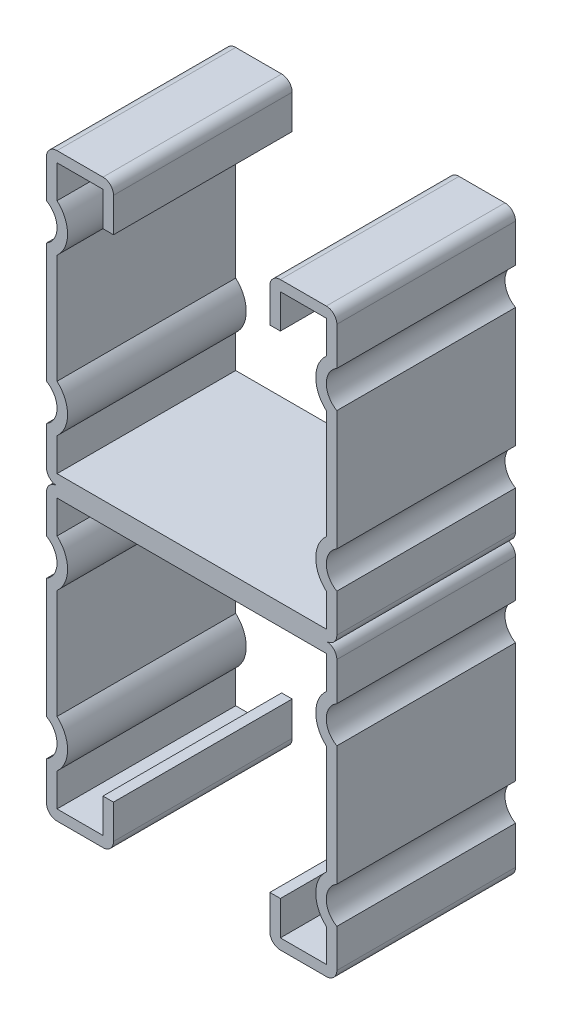
SolidWorks part; units mm, degrees
ref_plane "Plane1" through (0, 0, 0) normal (0, 0, 1) x (1, 0, 0)
ref_plane "Plane2" through (0, 0, 0) normal (0, 1, 0) x (1, 0, 0)
ref_plane "Plane3" through (0, 0, 0) normal (1, 0, 0) x (0, 0, -1)
sketch "Sketch1" plane through (0, 0, 0) normal (0, 0, 1) x (1, 0, 0)
  line L0 (-41.275, 39.7764) -> (-41.275, 34.3457)
  line L1 (-41.275, 29.1543) -> (-41.275, 12.1207)
  line L2 (-39.7764, 0) -> (-1.4986, 0)
  line L3 (0, 1.4986) -> (0, 6.9293)
  line L4 (0, 34.3457) -> (0, 39.7764)
  line L5 (-1.4986, 41.275) -> (-8.0264, 41.275)
  line L6 (-9.525, 39.7764) -> (-9.525, 34.925)
  line L7 (-39.7764, 41.275) -> (-33.2486, 41.275)
  line L8 (-31.75, 39.7764) -> (-31.75, 34.925)
  line L9 (-1.4986, 6.174) -> (-1.4986, 35.101) construction
  line L10 (-39.7764, 35.101) -> (-39.7764, 6.174) construction
  line L11 (-33.2486, 39.7764) -> (-33.2486, 34.925)
  line L12 (-39.7764, 39.7764) -> (-33.2486, 39.7764)
  line L13 (-39.7764, 39.7764) -> (-39.7764, 35.101)
  line L14 (-39.7764, 28.399) -> (-39.7764, 12.876)
  line L15 (-39.7764, 1.4986) -> (-1.4986, 1.4986)
  line L16 (-1.4986, 1.4986) -> (-1.4986, 6.174)
  line L17 (-1.4986, 35.101) -> (-1.4986, 39.7764)
  line L18 (-1.4986, 39.7764) -> (-8.0264, 39.7764)
  line L19 (-8.0264, 39.7764) -> (-8.0264, 34.925)
  line L20 (-33.2486, 34.925) -> (-31.75, 34.925)
  line L21 (-9.525, 34.925) -> (-8.0264, 34.925)
  line L22 (-10.16, 20.6375) -> (12.7, 20.6375) construction
  line L23 (-41.275, 6.9293) -> (-41.275, 1.4986)
  line L24 (-39.7764, 6.174) -> (-39.7764, 1.4986)
  line L25 (0, 12.1207) -> (0, 29.1543)
  line L26 (-1.4986, 12.876) -> (-1.4986, 28.399)
  arc A0 (0, 34.3457) -> (0, 29.1543) centre (1.4986, 31.75) ccw
  arc A1 (-41.275, 29.1543) -> (-41.275, 34.3457) centre (-42.7736, 31.75) ccw
  arc A2 (-33.2486, 41.275) -> (-31.75, 39.7764) centre (-33.2486, 39.7764) cw
  arc A3 (-41.275, 39.7764) -> (-39.7764, 41.275) centre (-39.7764, 39.7764) cw
  arc A4 (-39.7764, 0) -> (-41.275, 1.4986) centre (-39.7764, 1.4986) cw
  arc A5 (0, 1.4986) -> (-1.4986, 0) centre (-1.4986, 1.4986) cw
  arc A6 (-1.4986, 41.275) -> (0, 39.7764) centre (-1.4986, 39.7764) cw
  arc A7 (-9.525, 39.7764) -> (-8.0264, 41.275) centre (-8.0264, 39.7764) cw
  arc A8 (-39.7764, 28.399) -> (-39.7764, 35.101) centre (-42.7736, 31.75) ccw
  arc A9 (-1.4986, 35.101) -> (-1.4986, 28.399) centre (1.4986, 31.75) ccw
  arc A10 (0, 6.9293) -> (0, 12.1207) centre (1.4986, 9.525) cw
  arc A11 (-1.4986, 6.174) -> (-1.4986, 12.876) centre (1.4986, 9.525) cw
  arc A12 (-39.7764, 12.876) -> (-39.7764, 6.174) centre (-42.7736, 9.525) cw
  arc A13 (-41.275, 12.1207) -> (-41.275, 6.9293) centre (-42.7736, 9.525) cw
  dimension "D9" = 2.9972
  dimension "D10" = 2.9972
  dimension "Width" = 41.275
  dimension "D6" = 22.225
  dimension "edge" = 9.525
  dimension "Lip" = 6.35
  dimension "D2" = 9.525
  dimension "D1" = 41.275
  dimension "D3" = 20.6375
  dimension "gauge" = 1.4986
extrude "Base-Extrude" add sketch "Sketch1" along normal mid plane 25.4
mirror "Mirror1" about plane through (0, 0, 0) normal (0, 1, 0) of "Base-Extrude"
equation "\"D6@Sketch1\" = \"Width@Sketch1\" - 2 * \"edge@Sketch1\""
equation "\"D10@Sketch1\" = 2 * \"gauge@Sketch1\""
equation "\"D9@Sketch1\" = \"D10@Sketch1\""
equation "\"D2@Sketch1\" = \"edge@Sketch1\""
